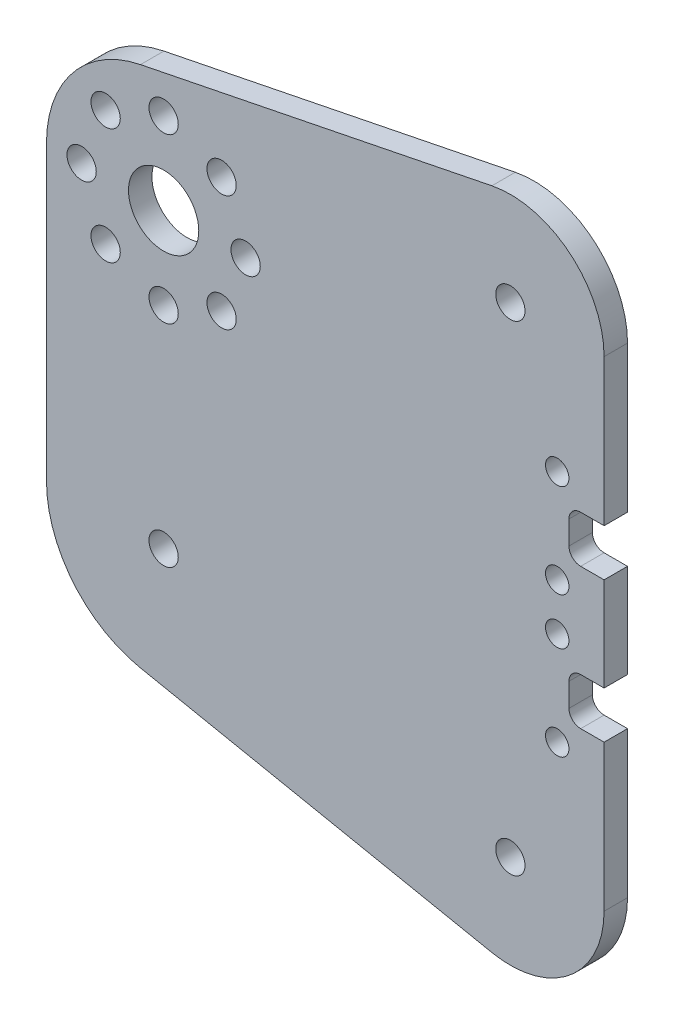
SolidWorks part; units mm, degrees
material "自訂玻璃纖維"
ref_plane "前基準面" through (0, 0, 0) normal (0, 0, 1) x (1, 0, 0)
ref_plane "上基準面" through (0, 0, 0) normal (0, 1, 0) x (1, 0, 0)
ref_plane "右基準面" through (0, 0, 0) normal (1, 0, 0) x (0, 0, -1)
sketch "草圖1" plane through (0, 0, 0) normal (0, 0, 1) x (1, 0, 0)
  line L0 (-28.5419, -16.118) -> (-28.5419, -41.118)
  line L1 (-20.5158, -6.3147) -> (9.479, -0.2754)
  line L2 (19.0581, -8.118) -> (19.0581, -20.618)
  line L3 (16.0581, -21.618) -> (16.0581, -23.618)
  line L4 (19.0581, -20.618) -> (17.0581, -20.618)
  line L5 (16.0581, -33.618) -> (16.0581, -35.618)
  line L6 (19.0581, -24.618) -> (17.0581, -24.618)
  line L7 (19.0581, -24.618) -> (19.0581, -32.618)
  line L8 (19.0581, -36.618) -> (17.0581, -36.618)
  line L9 (-20.5158, -50.9213) -> (9.479, -56.9606)
  line L10 (19.0581, -32.618) -> (17.0581, -32.618)
  line L11 (19.0581, -36.618) -> (19.0581, -49.118)
  circle A0 centre (-18.5419, -16.118) radius 3
  circle A1 centre (-18.5419, -9.118) radius 1.25
  circle A2 centre (-13.5922, -11.1682) radius 1.25
  circle A3 centre (-11.5419, -16.118) radius 1.25
  circle A4 centre (-13.5922, -21.0677) radius 1.25
  circle A5 centre (-18.5419, -23.118) radius 1.25
  circle A6 centre (-23.4917, -21.0677) radius 1.25
  circle A7 centre (-25.5419, -16.118) radius 1.25
  circle A8 centre (-23.4917, -11.1682) radius 1.25
  circle A9 centre (-18.5419, -41.118) radius 1.25
  arc A10 (19.0581, -49.118) -> (9.479, -56.9606) centre (11.0581, -49.118) cw
  circle A12 centre (11.0581, -8.118) radius 1.25
  arc A13 (-28.5419, -16.118) -> (-20.5158, -6.3147) centre (-18.5419, -16.118) cw
  arc A14 (19.0581, -8.118) -> (9.479, -0.2754) centre (11.0581, -8.118) ccw
  arc A15 (17.0581, -20.618) -> (16.0581, -21.618) centre (17.0581, -21.618) ccw
  arc A16 (16.0581, -23.618) -> (17.0581, -24.618) centre (17.0581, -23.618) ccw
  circle A18 centre (11.0581, -49.118) radius 1.25
  arc A20 (-28.5419, -41.118) -> (-20.5158, -50.9213) centre (-18.5419, -41.118) ccw
  circle A22 centre (15.0581, -26.618) radius 1
  circle A23 centre (15.0581, -18.618) radius 1
  circle A24 centre (15.0581, -38.618) radius 1
  circle A25 centre (15.0581, -30.618) radius 1
  arc A26 (16.0581, -35.618) -> (17.0581, -36.618) centre (17.0581, -35.618) ccw
  arc A27 (17.0581, -32.618) -> (16.0581, -33.618) centre (17.0581, -33.618) ccw
  point P3 (11.0581, -8.118)
  point P9 (-18.5419, -41.118)
  point P10 (19.0581, -49.118)
  point P24 (-18.5419, -16.118)
  point P25 (-8.5419, -16.118)
  point P26 (19.0581, -20.618)
  point P28 (-18.5419, -41.118)
  point P31 (-18.5419, -41.118)
  point P34 (-15.5419, -23.118)
  point P40 (15.0581, -28.618)
  point P46 (-18.5419, -38.118)
  point P51 (-18.5419, -41.118)
  point P61 (-18.5419, -30.118)
  dimension "D3" = 6
  dimension "D4" = 2.5
  dimension "D5" = 7
  dimension "D6" = 8
  dimension "D7" = 2.5
  dimension "D10" = 8
  dimension "D11" = 8
  dimension "D12" = 2
  dimension "D13" = 2
  dimension "D14" = 4
  dimension "D15" = 2
  dimension "D17" = 7.8426
  dimension "D9" = 2.5
  dimension "D2" = 3
extrude "填料-伸長2" add sketch "草圖1" along normal blind 2
